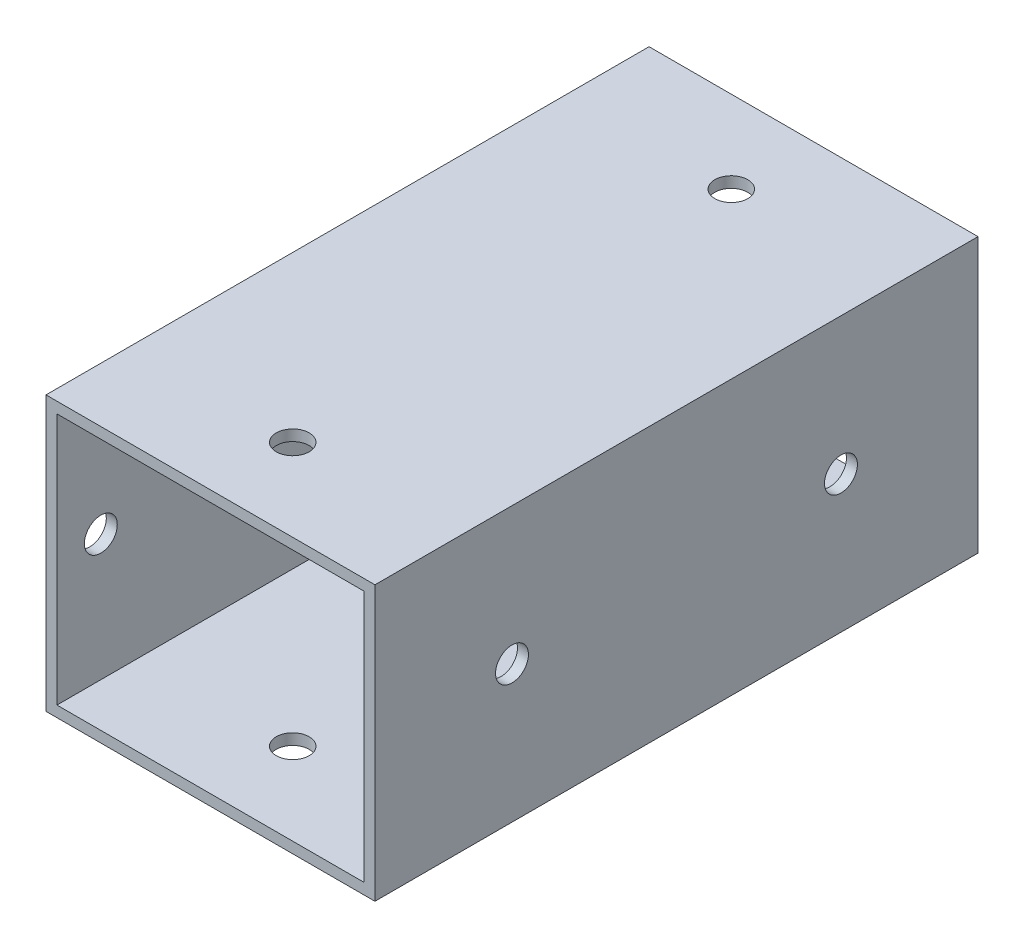
SolidWorks part; units mm, degrees
material "6063-T5"
ref_plane "前视基准面" through (0, 0, 0) normal (0, 0, 1) x (1, 0, 0)
ref_plane "上视基准面" through (0, 0, 0) normal (0, 1, 0) x (1, 0, 0)
ref_plane "右视基准面" through (0, 0, 0) normal (1, 0, 0) x (0, 0, -1)
other "Configuration Table"
sketch "草图1" plane through (0, 0, 0) normal (0, 0, 1) x (1, 0, 0)
  line L0 (-14, -11.5) -> (-14, 11.5)
  line L1 (-15, -12.5) -> (15, -12.5)
  line L2 (-15, -12.5) -> (-15, 12.5)
  line L3 (-15, 12.5) -> (15, 12.5)
  line L4 (15, -12.5) -> (15, 12.5)
  line L5 (0, 12.5) -> (0, -12.5) construction
  line L6 (-15, 0) -> (15, 0) construction
  line L7 (-14, 11.5) -> (14, 11.5)
  line L8 (14, -11.5) -> (14, 11.5)
  line L9 (-14, -11.5) -> (14, -11.5)
  point P0 (0, 0)
  dimension "D1" = 30
  dimension "D2" = 25
  dimension "D3" = 1
extrude "凸台-拉伸1" add sketch "草图1" along normal mid plane 55
sketch "草图2" plane through (0, 12.5, 0) normal (0, 1, 0) x (1, 0, 0)
  line L0 (0, -20) -> (0, 20) construction
  circle A0 centre (0, 20) radius 1.5
  circle A1 centre (0, -20) radius 1.5
  point P4 (0, 0)
  dimension "D2" = 3
  dimension "D1" = 40
extrude "切除-拉伸1" cut sketch "草图2" against normal blind 70
sketch "草图3" plane through (-14, 0, 0) normal (1, 0, 0) x (0, 0, -1)
  line L0 (0, 0) -> (0, 12.5) construction
  line L1 (-27.5, 12.5) -> (27.5, 12.5) construction
  circle A0 centre (0, 0) radius 1.5 construction
  circle A1 centre (-23.5, 0) radius 1.5 construction
  circle A2 centre (0, 0) radius 1.5
  circle A3 centre (-23.5, 0) radius 1.5
  circle A4 centre (23.5, 0) radius 1.5
extrude "切除-拉伸2" cut sketch "草图3" against normal blind 20
sketch "草图4" plane through (15, 0, 0) normal (1, 0, 0) x (0, 0, -1)
  line L0 (-15, 0) -> (15, 0) construction
  circle A0 centre (15, 0) radius 1.5
  circle A1 centre (-15, 0) radius 1.5
  point P4 (0, 0)
  dimension "D2" = 3
  dimension "D1" = 30
extrude "切除-拉伸3" cut sketch "草图4" against normal blind 20
sketch "草图5" [suppressed] plane through (0, -12.5, 0) normal (0, -1, 0) x (1, 0, 0)
  circle A0 centre (11, 31) radius 1.505 construction
  circle A1 centre (11, 9) radius 1.505 construction
  circle A2 centre (-11, 9) radius 1.505 construction
  circle A3 centre (-11, 31) radius 1.505 construction
  circle A4 centre (11, 31) radius 1.505
  circle A5 centre (11, 9) radius 1.505
  circle A6 centre (-11, 9) radius 1.505
  circle A7 centre (-11, 31) radius 1.505
  circle A8 centre (10, -35) radius 1.525 construction
  circle A9 centre (-10, -35) radius 1.525 construction
  circle A10 centre (10, 0) radius 1.525 construction
  circle A11 centre (-10, 0) radius 1.525 construction
  circle A12 centre (10, -35) radius 1.525
  circle A13 centre (-10, -35) radius 1.525
  circle A14 centre (10, 0) radius 1.525
  circle A15 centre (-10, 0) radius 1.525
extrude "切除-拉伸4" [suppressed] cut sketch "草图5" against normal up to surface (25 mm away)
